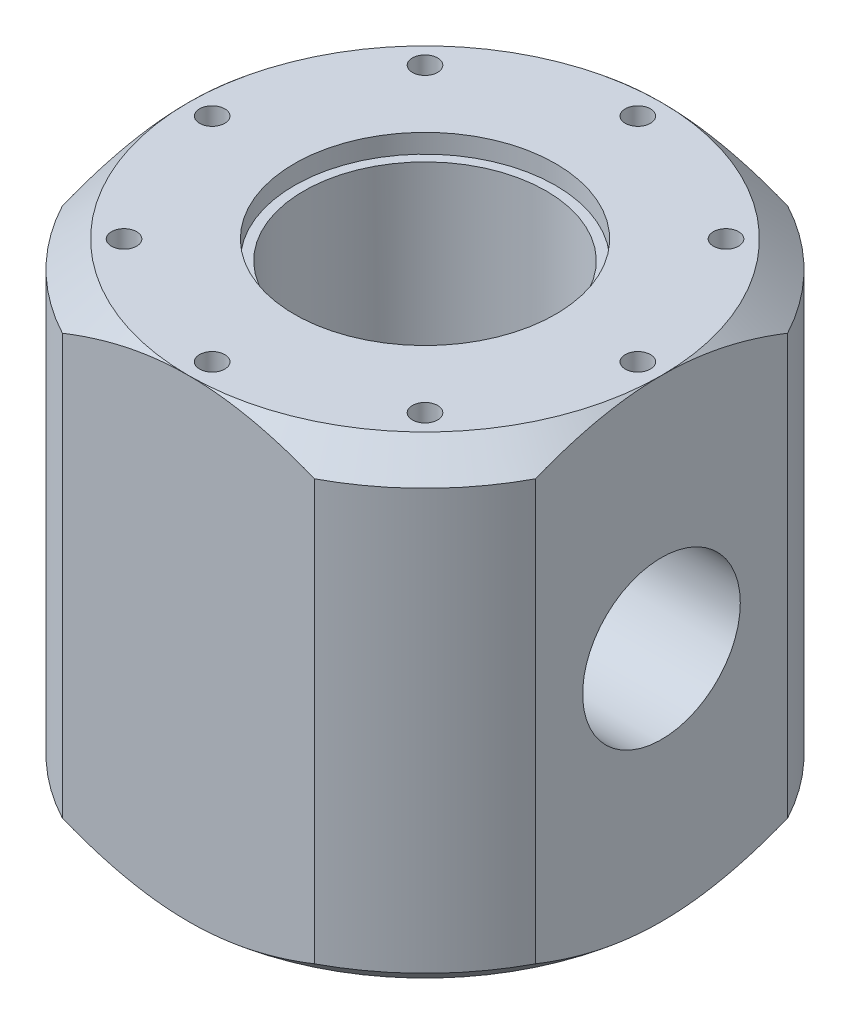
SolidWorks part; units mm, degrees
material "Alumina"
ref_plane "Front Plane" through (0, 0, 0) normal (0, 0, 1) x (1, 0, 0)
ref_plane "Top Plane" through (0, 0, 0) normal (0, 1, 0) x (1, 0, 0)
ref_plane "Right Plane" through (0, 0, 0) normal (1, 0, 0) x (0, 0, -1)
sketch "Sketch1" plane through (0, 0, 0) normal (0, 1, 0) x (1, 0, 0)
  line L0 (-37.5, -37.5) -> (37.5, -37.5)
  line L1 (-37.5, -37.5) -> (-37.5, 37.5)
  line L2 (37.5, -37.5) -> (37.5, 37.5)
  line L3 (-37.5, 37.5) -> (37.5, 37.5)
  line L4 (-37.5, -37.5) -> (37.5, 37.5) construction
  line L5 (37.5, -37.5) -> (-37.5, 37.5) construction
  point P1 (0, 0)
  dimension "D1" = 75
  dimension "D2" = 75
extrude "Boss-Extrude1" add sketch "Sketch1" along normal blind 75
sketch "Sketch2" plane through (0, 0, 0) normal (0, -1, 0) x (-1, 0, 0)
  circle A0 centre (0, 0) radius 5.35
  dimension "D1" = 10.7
extrude "Cut-Extrude1" cut sketch "Sketch2" against normal through all
sketch "Sketch5" plane through (37.5, 0, 0) normal (1, 0, 0) x (0, 0, -1)
  line L0 (0, 0) -> (0, 75) construction
  line L1 (-37.5, 0) -> (37.5, 0) construction
  line L2 (-37.5, 75) -> (37.5, 75) construction
  line L3 (-37.5, 37.5) -> (37.5, 37.5) construction
  line L4 (-37.5, 75) -> (-37.5, 0) construction
  line L5 (37.5, 75) -> (37.5, 0) construction
  circle A0 centre (0, 37.5) radius 12.5
  dimension "D1" = 25
extrude "Cut-Extrude2" cut sketch "Sketch5" against normal through all
sketch "Sketch7" plane through (0, 0, 0) normal (0, -1, 0) x (1, 0, 0)
  circle A0 centre (0, 0) radius 19.21
  circle A1 centre (0, 0) radius 20.71
  dimension "D1" = 38.42
  dimension "D2" = 41.42
extrude "Cut-Extrude3" cut sketch "Sketch7" against normal blind 3
sketch "Sketch8" plane through (0, 0, 0) normal (0, -1, 0) x (1, 0, 0)
  line L4 (-37.5, 37.5) -> (-37.5, -37.5)
  line L5 (-37.5, -37.5) -> (37.5, -37.5)
  line L6 (37.5, -37.5) -> (37.5, 37.5)
  line L7 (37.5, 37.5) -> (-37.5, 37.5)
  line L8 (-37.5, 37.5) -> (-37.5, -37.5)
  line L9 (-37.5, -37.5) -> (37.5, -37.5)
  line L10 (37.5, -37.5) -> (37.5, 37.5)
  line L11 (37.5, 37.5) -> (-37.5, 37.5)
  circle A0 centre (0, 0) radius 20.71 construction
  circle A1 centre (0, 0) radius 20.71
  circle A2 centre (0, 0) radius 30
  dimension "D2" = 37.5
  dimension "D3" = 41.42
  dimension "D4" = 60
  dimension "D1" = 0
sketch "Sketch11" plane through (0, 0, 0) normal (0, -1, 0) x (1, 0, 0)
  line L0 (-37.5, 37.5) -> (-37.5, -37.5) construction
  circle A0 centre (-33.75, 0) radius 2
  circle A1 centre (-23.8649, 23.8649) radius 2
  circle A2 centre (0, 33.75) radius 2
  circle A3 centre (23.8649, 23.8649) radius 2
  circle A4 centre (33.75, 0) radius 2
  circle A5 centre (23.8649, -23.8649) radius 2
  circle A6 centre (0, -33.75) radius 2
  circle A7 centre (-23.8649, -23.8649) radius 2
  point P16 (0, 0)
  dimension "D1" = 4
  dimension "D2" = 3.75
  dimension "D3" = 8
extrude "Cut-Extrude4" cut sketch "Sketch11" against normal blind 10
ref_plane "Plane1" through (0, 37.5, 0) normal (0, 1, 0) x (1, 0, 0)
mirror "Mirror1" about plane through (0, 37.5, 0) normal (0, 1, 0) of "Cut-Extrude3", "Cut-Extrude4"
sketch "Sketch14" plane through (0, 0, 0) normal (0, -1, 0) x (1, 0, 0)
  circle A0 centre (0, 0) radius 37.5
sketch "Sketch12" plane through (0, 0, 0) normal (0, -1, 0) x (1, 0, 0)
  circle A2 centre (0, 0) radius 42.5
  circle A3 centre (0, 0) radius 42.5
  dimension "D1" = 5
extrude "Cut-Extrude6" cut sketch "Sketch12" against normal through all flip side to cut
sketch "Sketch13" plane through (0, 75, 0) normal (0, 1, 0) x (1, 0, 0)
  circle A0 centre (0, 0) radius 19.21 construction
  circle A1 centre (0, 0) radius 19.21
extrude "Cut-Extrude7" cut sketch "Sketch13" against normal blind 50
sketch "Sketch17" [suppressed] plane through (0, 0, 0) normal (0, 1, 0) x (1, 0, 0)
  circle A1 centre (0, 0) radius 37.5
  circle A2 centre (0, 0) radius 37.5
  circle A3 centre (0, 0) radius 42.5
  circle A4 centre (0, 0) radius 42.5
  dimension "D1" = 0
  dimension "D2" = 0
sketch "Sketch15" [suppressed] plane through (0, 0, -37.5) normal (0, 0, -1) x (-1, 0, 0)
  line L0 (-20, 5) -> (20, 5) construction
  line L1 (-20, 0) -> (-20, 75) construction
  line L2 (20, 75) -> (20, 0) construction
  line L3 (-20, 0) -> (20, 0) construction
  text T0 "IISER M" font "Consolas" height 3.5
  dimension "D1" = 5
extrude "Boss-Extrude2" [suppressed] add sketch "Sketch15" along normal blind 1
sketch "Sketch16" plane through (0, 0, 0) normal (0, 1, 0) x (1, 0, 0)
  circle A1 centre (0, 0) radius 37.5
  circle A2 centre (0, 0) radius 37.5
  dimension "D1" = 0
extrude "Cut-Extrude8" cut sketch "Sketch16" along normal blind 10 draft 50 flip side to cut
mirror "Mirror2" about plane through (0, 37.5, 0) normal (0, 1, 0) of "Cut-Extrude8"
sketch "Sketch18" plane through (0, 0, 0) normal (0, 1, 0) x (1, 0, 0)
  line L0 (10, 37.5) -> (9.9975, 36.1428)
  line L1 (37.5, 10) -> (36.1424, 9.999)
  line L2 (37.5, -10) -> (36.1428, -9.9975)
  line L3 (37.5, -20) -> (37.5, -10)
  line L4 (20, 37.5) -> (-20, 37.5)
  line L5 (37.5, -20) -> (37.5, 20)
  line L6 (-20, -37.5) -> (20, -37.5)
  line L7 (-37.5, 20) -> (-37.5, -20)
  line L8 (20, 37.5) -> (10, 37.5)
  line L9 (37.5, 10) -> (37.5, 20)
  line L10 (10, -37.5) -> (20, -37.5)
  line L11 (10, -37.5) -> (9.999, -36.1424)
  line L12 (-10, -37.5) -> (-9.9975, -36.1428)
  line L13 (-20, -37.5) -> (-10, -37.5)
  line L14 (-37.5, -10) -> (-37.5, -20)
  line L15 (-37.5, -10) -> (-36.1424, -9.999)
  line L16 (-37.5, 10) -> (-36.1428, 9.9975)
  line L17 (-37.5, 20) -> (-37.5, 10)
  line L18 (-10, 37.5) -> (-20, 37.5)
  line L19 (-10, 37.5) -> (-9.999, 36.1424)
  arc A0 (36.1424, 9.999) -> (9.9975, 36.1428) centre (0, 0) ccw
  arc A1 (9.999, -36.1424) -> (36.1428, -9.9975) centre (0, 0) ccw
  arc A2 (20, -37.5) -> (37.5, -20) centre (0, 0) ccw
  arc A3 (-36.1424, -9.999) -> (-9.9975, -36.1428) centre (0, 0) ccw
  arc A4 (-37.5, -20) -> (-20, -37.5) centre (0, 0) ccw
  arc A5 (-9.999, 36.1424) -> (-36.1428, 9.9975) centre (0, 0) ccw
  arc A6 (37.5, 20) -> (20, 37.5) centre (0, 0) ccw
  arc A7 (20, -37.5) -> (37.5, -20) centre (0, 0) ccw
  arc A8 (-37.5, -20) -> (-20, -37.5) centre (0, 0) ccw
  arc A9 (-20, 37.5) -> (-37.5, 20) centre (0, 0) ccw
  arc A10 (37.5, 20) -> (20, 37.5) centre (0, 0) ccw
  arc A11 (-20, 37.5) -> (-37.5, 20) centre (0, 0) ccw
  point P38 (0, 0)
  dimension "D1" = 4
  dimension "D2" = 0
extrude "Boss-Extrude4" [suppressed] add sketch "Sketch18" against normal blind 8
mirror "Mirror3" [suppressed] about plane through (0, 37.5, 0) normal (0, 1, 0)
